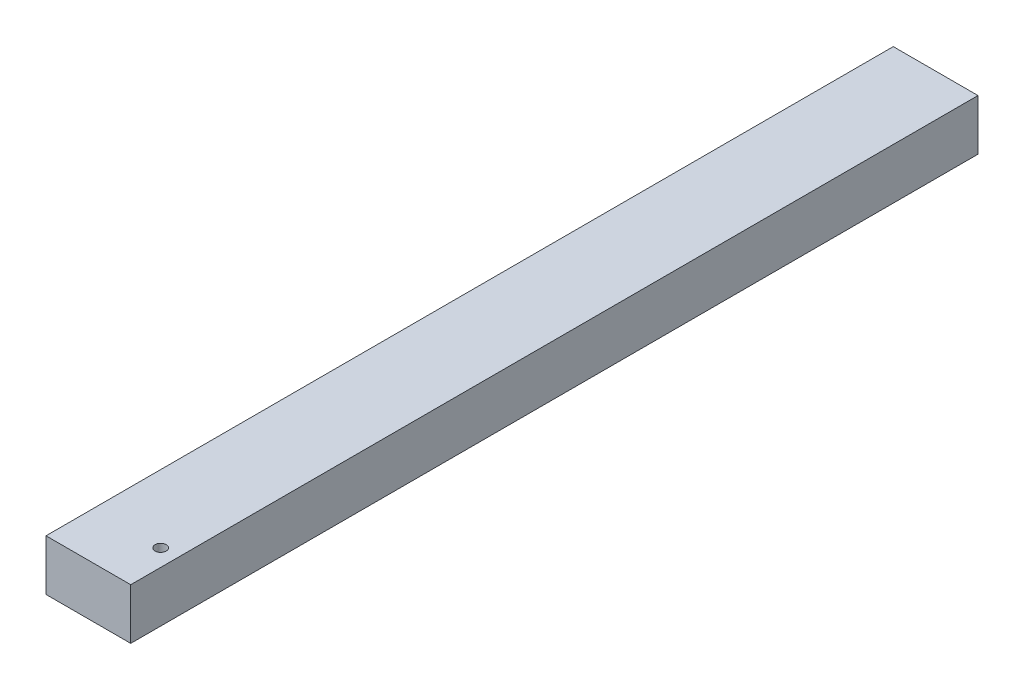
SolidWorks part; units mm, degrees
ref_plane "Front Plane" through (0, 0, 0) normal (0, 0, 1) x (1, 0, 0)
ref_plane "Top Plane" through (0, 0, 0) normal (0, 1, 0) x (1, 0, 0)
ref_plane "Right Plane" through (0, 0, 0) normal (1, 0, 0) x (0, 0, -1)
sketch "Sketch1" plane through (0, 0, 0) normal (0, 0, 1) x (1, 0, 0)
  line L1 (0, 0) -> (-50, 0)
  line L2 (0, 0) -> (0, 30)
  line L3 (0, 30) -> (-50, 30)
  line L4 (-50, 0) -> (-50, 30)
  dimension "D1" = 50
  dimension "D2" = 30
extrude "Boss-Extrude1" add sketch "Sketch1" along normal blind 500
sketch "Sketch2" plane through (0, 30, 0) normal (0, 1, 0) x (1, 0, 0)
  line L0 (-10, 0) -> (-10, -500) construction
  line L1 (0, 0) -> (-50, 0) construction
  line L2 (0, -500) -> (-50, -500) construction
  line L3 (0, -500) -> (0, 0) construction
  point P8 (-10, -472.328)
  dimension "D1" = 10
hole_wizard "M6 Clearance Hole1" positions "3DSketch1" profile "Sketch3" hole size "M6" standard "ISO" end condition through all
sketch3d "3DSketch1"
  point P0 (-10, 30, 472.328)
sketch "Sketch3" plane through (-10, 30, 472.328) normal (1, 0, 0) x (0, 0, 1)
  line L0 (0, 0) -> (0, 30)
  line L1 (0, 30) -> (3.3, 30)
  line L2 (3.3, 30) -> (3.3, 0)
  line L5 (3.3, 0) -> (0, 0)
  line L11 (0, -6.35) -> (0, 107.95) construction
  dimension "Thru Hole Dia." = 6.6
  dimension "Thru Hole Depth" = 30
